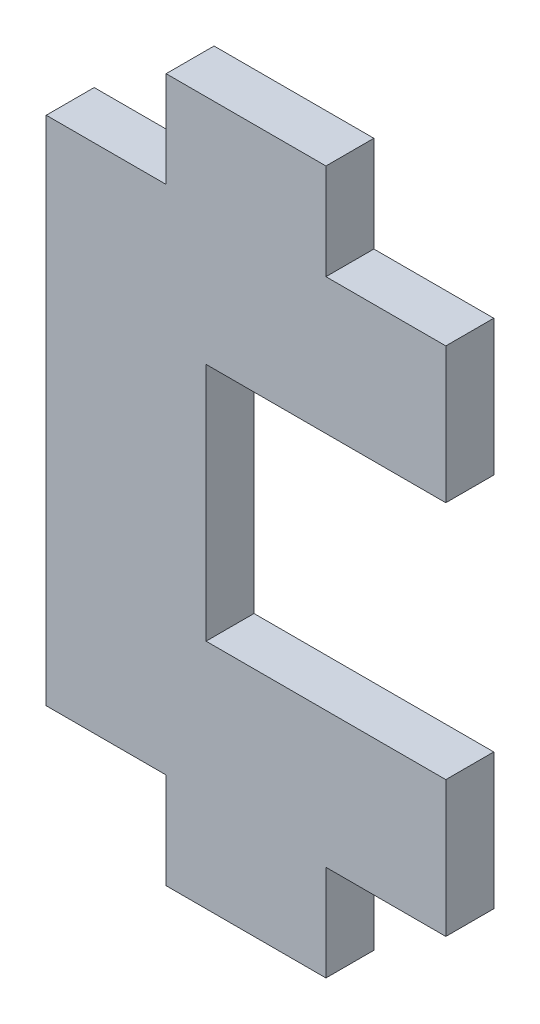
SolidWorks part; units mm, degrees
ref_plane "Plano frontal" through (0, 0, 0) normal (0, 0, 1) x (1, 0, 0)
ref_plane "Plano superior" through (0, 0, 0) normal (0, 1, 0) x (1, 0, 0)
ref_plane "Plano direito" through (0, 0, 0) normal (1, 0, 0) x (0, 0, -1)
sketch "Esboço1" plane through (0, 0, 0) normal (0, 0, 1) x (1, 0, 0)
  line L0 (0, 0) -> (12.5, 0) construction
  line L1 (-12.5, -16) -> (12.5, -16)
  line L2 (-12.5, -16) -> (-12.5, 16)
  line L3 (-12.5, 16) -> (12.5, 16)
  line L4 (12.5, -16) -> (12.5, 16)
  line L5 (-12.5, -16) -> (12.5, 16) construction
  line L6 (-12.5, 16) -> (12.5, -16) construction
  line L7 (5, 22) -> (-5, 22)
  line L8 (5, 22) -> (5, 16)
  line L9 (5, 16) -> (-5, 16)
  line L10 (-5, 22) -> (-5, 16)
  line L11 (5, 22) -> (-5, 16) construction
  line L12 (5, 16) -> (-5, 22) construction
  line L13 (5, -16) -> (-5, -16)
  line L14 (-5, -22) -> (-5, -16)
  line L15 (5, -22) -> (-5, -22)
  line L16 (5, -22) -> (5, -16)
  line L17 (-2.5, -7.5) -> (-2.5, 7.5)
  line L18 (-2.5, 7.5) -> (12.5, 7.5)
  line L19 (-2.5, -7.5) -> (12.5, -7.5)
  point P0 (0, 0)
  point P6 (0, 19)
  point P19 (-2.5, 0)
  point P21 (1.816, -7.5)
  point P23 (0, 0)
  dimension "D1" = 10
  dimension "D2" = 6
  dimension "D3" = 15
  dimension "D4" = 10
  dimension "D5" = 32
  dimension "D6" = 15
extrude "Ressalto-extrusão1" add sketch "Esboço1" along normal blind 3 contours L19 L17 L18 L4 L3 L2 L1 | L7 L10 L3 L8 | L15 L16 L1 L14
